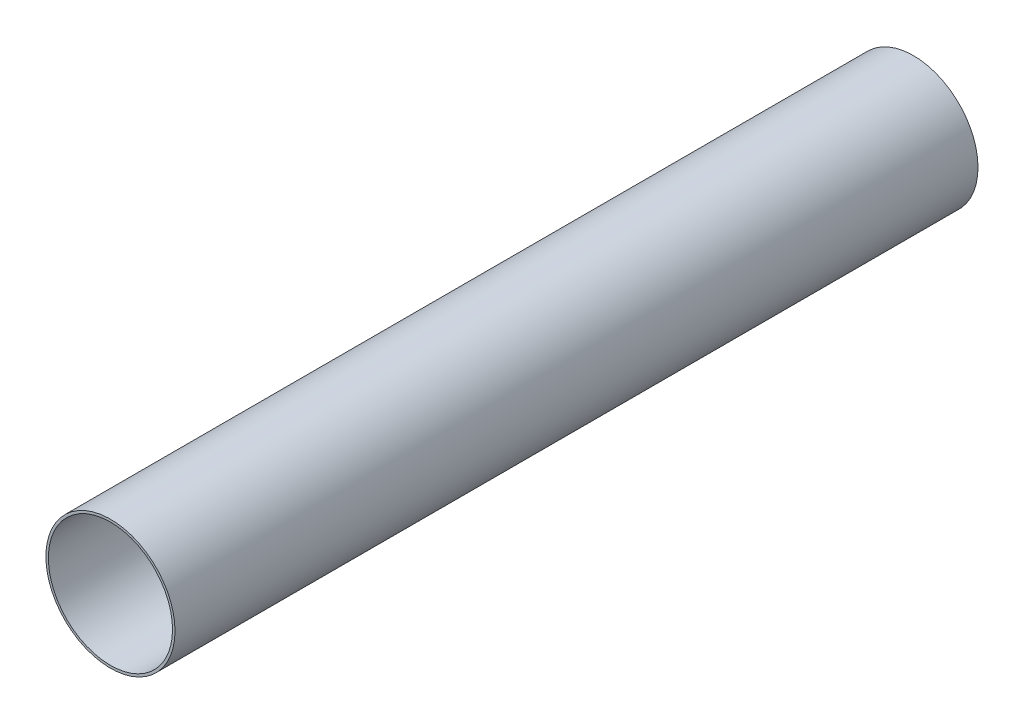
SolidWorks part; units mm, degrees
ref_plane "Front Plane" through (0, 0, 0) normal (0, 0, 1) x (1, 0, 0)
ref_plane "Top Plane" through (0, 0, 0) normal (0, 1, 0) x (1, 0, 0)
ref_plane "Right Plane" through (0, 0, 0) normal (1, 0, 0) x (0, 0, -1)
sketch "Sketch1" plane through (0, 0, 0) normal (0, 0, 1) x (1, 0, 0)
  circle A0 centre (0, 0) radius 75
  circle A1 centre (0, 0) radius 78
  dimension "D1" = 3
extrude "Boss-Extrude1" add sketch "Sketch1" against normal blind 970
